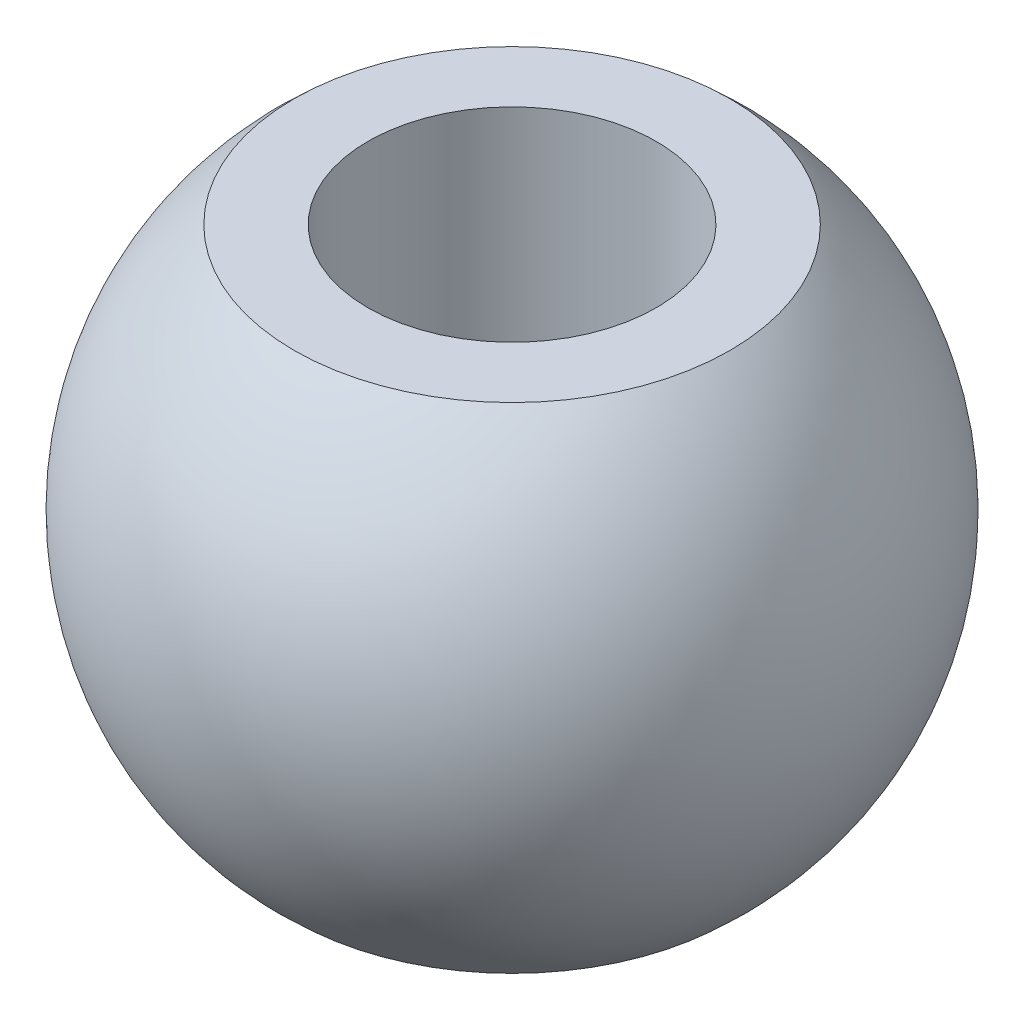
SolidWorks part; units mm, degrees
ref_plane "Plan de face" through (0, 0, 0) normal (0, 0, 1) x (1, 0, 0)
ref_plane "Plan de dessus" through (0, 0, 0) normal (0, 1, 0) x (1, 0, 0)
ref_plane "Plan de droite" through (0, 0, 0) normal (1, 0, 0) x (0, 0, -1)
sketch "Esquisse1" plane through (0, 0, 0) normal (0, 0, 1) x (1, 0, 0)
  line L0 (0, 3.8943) -> (0, -2.5825) construction
  line L1 (-1.75, 3) -> (-1.75, -3)
  line L2 (-1.75, -3) -> (-2.6458, -3)
  line L3 (-1.75, 3) -> (-2.6458, 3)
  arc A0 (-2.6458, 3) -> (-2.6458, -3) centre (0, 0) ccw
  point P8 (-1.75, 0)
  dimension "D3" = 4
  dimension "D1" = 1.75
  dimension "D2" = 6
revolve "Révolution1" add sketch "Esquisse1" angle 360 about L0
